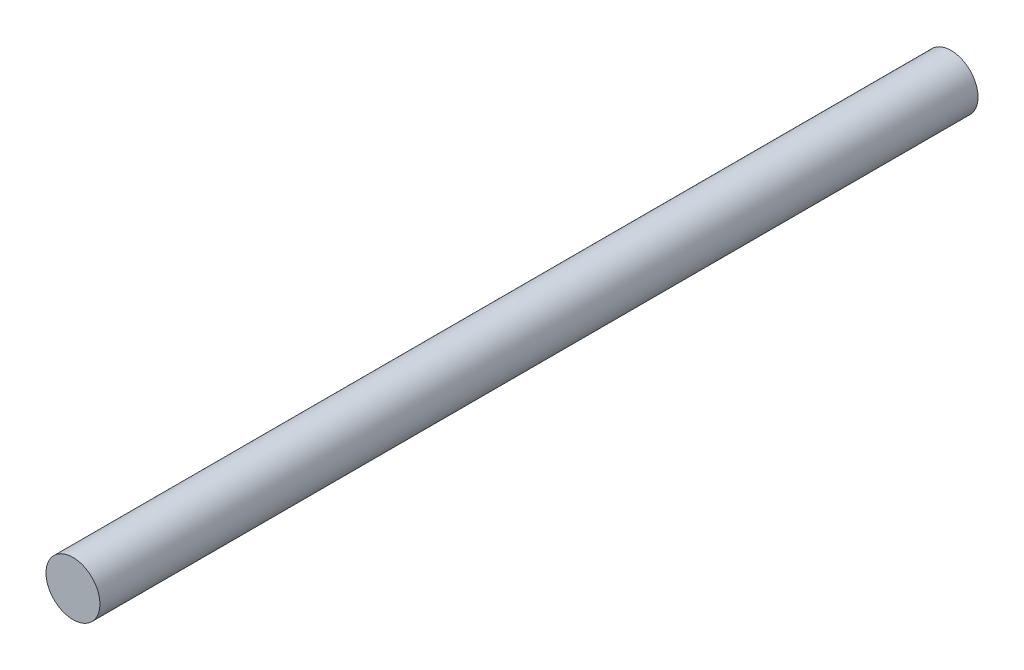
SolidWorks part; units mm, degrees
material "Stal węglowa"
ref_plane "Płaszczyzna przednia" through (0, 0, 0) normal (0, 0, 1) x (1, 0, 0)
ref_plane "Płaszczyzna górna" through (0, 0, 0) normal (0, 1, 0) x (1, 0, 0)
ref_plane "Płaszczyzna prawa" through (0, 0, 0) normal (1, 0, 0) x (0, 0, -1)
sketch "Szkic1" plane through (0, 0, 0) normal (0, 0, 1) x (1, 0, 0)
  circle A0 centre (0, 0) radius 3.5
  dimension "D1" = 7
extrude "Dodanie-wyciągnięcie1" add sketch "Szkic1" along normal blind 114
